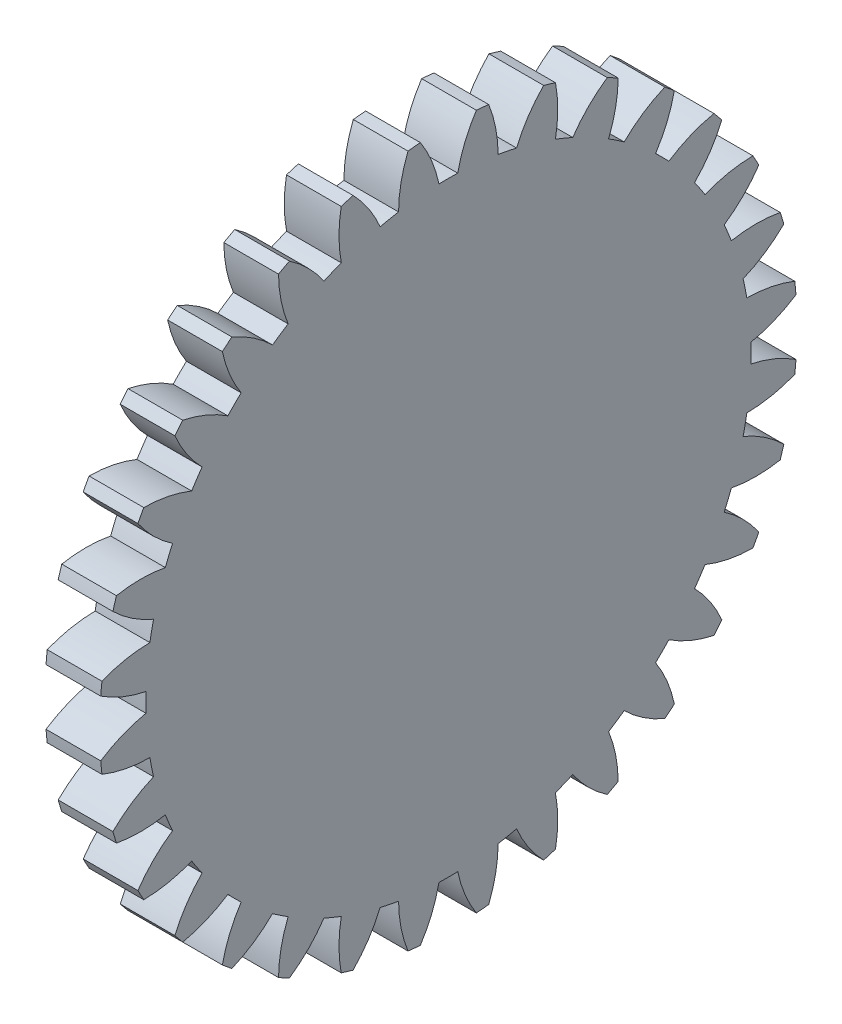
SolidWorks part; units mm, degrees
ref_plane "Plane1" through (0, 0, 0) normal (0, 0, 1) x (1, 0, 0)
ref_plane "Plane2" through (0, 0, 0) normal (0, 1, 0) x (1, 0, 0)
ref_plane "Plane3" through (0, 0, 0) normal (1, 0, 0) x (0, 0, -1)
other "Configuration Table"
sketch "HoldingSke" plane through (0, 0, 0) normal (0, 1, 0) x (1, 0, 0)
  line L0 (0, 0) -> (0.5654, -0.3533)
  line L1 (-15, 0) -> (100, 0) construction
  line L2 (0, 0) -> (-2.1039, 2.3779)
  line L3 (0, 0) -> (-11.863, 4.5341)
  line L4 (0, 0) -> (7.3237, 4.5764)
  line L5 (0, 0) -> (-46.8476, -17.4728)
  line L6 (0, 0) -> (-3.3159, -2.2372)
  line L7 (-2.1039, 2.3779) -> (8.6586, 51.2059)
  line L8 (-76.2, 54.61) -> (-75.3, 54.61)
  line L9 (-71.009, 38.7566) -> (-53.1078, 45.2721)
  line L10 (-76.2, 71.12) -> (104.1128, 71.12)
  line L11 (0, 0) -> (-4, 0)
  line L12 (-76.2, 101.6) -> (-76.147, 101.6)
  line L13 (24.9733, 27.94) -> (52.9518, 28.4284)
  line L14 (24.9733, 27.94) -> (24.9743, 27.94)
  line L15 (24.9733, 27.94) -> (100.4006, 29.5858)
  line L16 (-63.627, -1.5) -> (-12.827, -1.5)
  circle A0 centre (0, 0) radius 2.5
  circle A1 centre (0, 0) radius 22.124
  circle A2 centre (0, 0) radius 37.5
  circle A3 centre (0, 0) radius 2.5
  dimension "MHD" = 44.248
  dimension "Hub_dia" = 75
  dimension "Bore" = 5
  dimension "MBD" = 5
  dimension "Num_teeth" = 32
  dimension "Pitch" = 0.6667
  dimension "Overall_len" = 50
  dimension "Show_teeth" = 32
  dimension "Thickness" = 4
  dimension "OAL" = 50.0001
  dimension "T_dim" = 0.9
  dimension "Ap" = 20
  dimension "H" = 19.05
  dimension "Pitch_radius" = 180.3128
  dimension "Width" = 4
  dimension "Backlash" = 0.053
  dimension "Addendum_fac" = 1
  dimension "Dedendum_fac" = 1.25
  dimension "Clearance_fac" = 0.25
  dimension "Dedendum_add" = 0.001
  dimension "Module" = 1.5
sketch "BasProSke" plane through (0, 0, 0) normal (0, 1, 0) x (1, 0, 0)
  line L0 (-10, 0) -> (60, 0) construction
  line L1 (0, 0) -> (0, 25.5)
  line L2 (0, 0) -> (4, 0)
  line L3 (4, 0) -> (4, 25.5)
  line L4 (4, 25.5) -> (0, 25.5)
  dimension "Thickness" = 4
  dimension "Diameter" = 51
revolve "Base-Revolve" add sketch "BasProSke" angle 360 about L0
sketch "TooCutSke" plane through (0, 0, 0) normal (1, 0, 0) x (0, 0, -1)
  line L1 (0, 0) -> (0, 107) construction
  line L2 (0, 0) -> (-1.2704, 23.9664) construction
  line L3 (0, 0) -> (-4.7, 47.72) construction
  line L4 (-1.2704, 23.9664) -> (-2.35, 23.86) construction
  arc A0 (0.6867, 22.1133) -> (-0.6867, 22.1133) centre (0, 0) ccw
  arc A1 (2.0647, 25.4418) -> (-2.0647, 25.4418) centre (0, 0) ccw
  circle A2 centre (0, 0) radius 24 construction
  circle A3 centre (0, 0) radius 22.5526 construction
  arc A4 (-0.6867, 22.1133) -> (-2.0647, 25.4418) centre (-10.0881, 20.1706) ccw
  arc A5 (2.0647, 25.4418) -> (0.6867, 22.1133) centre (10.0881, 20.1706) ccw
  dimension "Root_dia" = 44.248
  dimension "Overcut_dia" = 51.0508
  dimension "Pitch_dia" = 48
  dimension "Base_dia" = 45.1052
  dimension "Flank_rad" = 9.6
  dimension "Half_ang" = 5.625
  dimension "Half_CT" = 1.0849
extrude "ToothCut" cut sketch "TooCutSke" along normal through all
fillet "Breaks" [suppressed] radius 0.03
fillet "RootFillets" [suppressed] radius 0.376
pattern_circular "TeethCuts" count 32 every 11.25 about axis through (-10, 0, 0) along (1, 0, 0) of "ToothCut", "RootFillets", "Breaks"
sketch "HubNeaOneSke" plane through (0, 0, 0) normal (-1, 0, 0) x (0, 0, 1)
  circle A0 centre (0, 0) radius 22.124
  dimension "Diameter" = 44.248
extrude "HubNearOne" [suppressed] add sketch "HubNeaOneSke" along normal blind 46.0001
sketch "HubNeaBotSke" plane through (0, 0, 0) normal (-1, 0, 0) x (0, 0, 1)
  circle A0 centre (0, 0) radius 22.124
  dimension "Diameter" = 44.248
extrude "HubNearBoth" [suppressed] add sketch "HubNeaBotSke" along normal blind 23
ref_plane "FarPln" through (4, 0, 0) normal (1, 0, 0) x (0, 0, -1)
sketch "HubFarSke" plane through (4, 0, 0) normal (1, 0, 0) x (0, 0, -1)
  circle A0 centre (0, 0) radius 22.124
  dimension "Diameter" = 44.248
extrude "HubFar" [suppressed] add sketch "HubFarSke" along normal blind 23
sketch "BorSke" plane through (0, 0, 0) normal (1, 0, 0) x (0, 0, -1)
  circle A0 centre (0, 0) radius 2.5
  dimension "Diameter" = 5
extrude "Bore" cut sketch "BorSke" along normal mid plane 100.0001
sketch "KeySke" plane through (0, 0, 0) normal (1, 0, 0) x (0, 0, -1)
  line L0 (-1, 0) -> (-1, 3.4)
  line L1 (-1, 3.4) -> (1, 3.4)
  line L2 (1, 3.4) -> (1, 0)
  line L3 (0, 0) -> (0, 34) construction
  line L4 (-1, 0) -> (1, 0)
  dimension "Offset" = 3.4
  dimension "Width" = 2
extrude "Keyway" [suppressed] cut sketch "KeySke" along normal mid plane 100.0001
pattern_circular "Keyway2" [suppressed] count 2 every 90 about axis through (-10, 0, 0) along (1, 0, 0)
sketch "Sketch1" plane through (0, 0, 0) normal (-1, 0, 0) x (0, 0, 1)
  circle A0 centre (0, 0) radius 2.5 construction
  circle A1 centre (0, 0) radius 2.5
extrude "Boss-Extrude1" add sketch "Sketch1" against normal up to surface (4 mm away) up to face at (4, 0, 2.5)
sketch "Sketch2" plane through (0, 0, 0) normal (-1, 0, 0) x (0, 0, 1)
  circle A0 centre (0, 0) radius 7.2
  dimension "D1" = 14.4
extrude "Cut-Extrude1" cut sketch "Sketch2" against normal blind 2
equation "' \"Module@HoldingSke\" = 6.35"
equation "' \"Num_teeth@HoldingSke\" = 12"
equation "' \"Ap@HoldingSke\" =  20"
equation "' \"Ap@HoldingSke\" = 20"
equation "' \"Width@HoldingSke\" = 0.5 * 25.4"
equation "' \"Hub_dia@HoldingSke\"= 1 * 25.4"
equation "' \"Hub_dia@HoldingSke\" = 1 * 25.4"
equation "' \"Overall_len@HoldingSke\" = 1.0 * 25.4"
equation "' \"Bore@HoldingSke\" = 0.75 * 25.4"
equation "' \"T_dim@HoldingSke\" = 0.1 * 25.4"
equation "' \"Width@KeySke\" = 0.25 * 25.4"
equation "' \"Show_teeth@HoldingSke\" = 13"
equation "' \"Backlash@HoldingSke\" = 0.009 * 25.4"
equation "' \"Addendum_fac@HoldingSke\" = 1.0"
equation "' \"Dedendum_fac@HoldingSke\" = 1.25"
equation "' \"Dedendum_add@HoldingSke\" = 0.00005 * 25.4"
equation "' \"Clearance_fac@HoldingSke\" = 0.25"
equation "\"Pitch@HoldingSke\" = 1 / \"Module@HoldingSke\""
equation "\"Overcut_dia@TooCutSke\" = (\"Num_teeth@HoldingSke\" + 2 * \"Addendum_fac@HoldingSke\") / \"Pitch@HoldingSke\" + 0.002 * 25.4"
equation "\"Pitch_dia@TooCutSke\" = \"Num_teeth@HoldingSke\" / \"Pitch@HoldingSke\""
equation "\"Base_dia@TooCutSke\" = \"Num_teeth@HoldingSke\" / \"Pitch@HoldingSke\" * cos((\"Ap@HoldingSke\"  * 3.14159265 / 180))"
equation "\"Root_dia@TooCutSke\" = (\"Num_teeth@HoldingSke\" + 2) / \"Pitch@HoldingSke\" - 2 * (\"Addendum_fac@HoldingSke\" + \"Dedendum_fac@HoldingSke\") / \"Pitch@HoldingSke\" - \"Dedendum_add@HoldingSke\" * 2"
equation "\"Half_ang@TooCutSke\" = 180 / \"Num_teeth@HoldingSke\""
equation "\"Half_CT@TooCutSke\" = \"Num_teeth@HoldingSke\" / \"Pitch@HoldingSke\" * sin((3.14159265 / 2 / \"Num_teeth@HoldingSke\")) / 2 - 7 * \"Backlash@HoldingSke\" / 4"
equation "\"Flank_rad@TooCutSke\" = \"Num_teeth@HoldingSke\" / \"Pitch@HoldingSke\" / 5"
equation "\"Radius@RootFillets\" = \"Clearance_fac@HoldingSke\" / \"Pitch@HoldingSke\" + \"Dedendum_add@HoldingSke\""
equation "\"Break_rad@Breaks\" = 0.02 / \"Pitch@HoldingSke\""
equation "\"Thickness@HoldingSke\" = \"Width@HoldingSke\""
equation "\"OAL@HoldingSke\" = \"Thickness@HoldingSke\""
equation "\"MHD@HoldingSke\" = (\"Num_teeth@HoldingSke\" + 2) / \"Pitch@HoldingSke\" - 2 * (\"Addendum_fac@HoldingSke\" + \"Dedendum_fac@HoldingSke\")  / \"Pitch@HoldingSke\" - \"Dedendum_add@HoldingSke\" * 2"
equation "\"MBD@HoldingSke\" = (\"Num_teeth@HoldingSke\" + 2) / \"Pitch@HoldingSke\" - 2 * (\"Addendum_fac@HoldingSke\" + \"Dedendum_fac@HoldingSke\")  / \"Pitch@HoldingSke\" - \"Dedendum_add@HoldingSke\" * 2 - 0.002 * 25.4"
equation "\"MHD@HoldingSke\" = ((sgn( \"MHD@HoldingSke\" - \"Hub_dia@HoldingSke\" )-1)*( \"MHD@HoldingSke\" - \"Hub_dia@HoldingSke\" ))/-2+ \"Hub_dia@HoldingSke\""
equation "\"MBD@HoldingSke\" = ((sgn( \"MBD@HoldingSke\" - \"Bore@HoldingSke\" )-1)*( \"MBD@HoldingSke\" - \"Bore@HoldingSke\" ))/-2+ \"Bore@HoldingSke\""
equation "\"OAL@HoldingSke\" = ((sgn( \"OAL@HoldingSke\" - \"Overall_len@HoldingSke\" )+1)*( \"OAL@HoldingSke\" - \"Overall_len@HoldingSke\" ))/2 + \"Overall_len@HoldingSke\" + 0.000002 * 25.4"
equation "\"Num_teeth@TeethCuts\" = int( \"Show_teeth@HoldingSke\" ) + 1"
equation "\"Num_teeth@TeethCuts\" = ((sgn( \"Num_teeth@TeethCuts\" - \"Num_teeth@HoldingSke\" )-1)*( \"Num_teeth@TeethCuts\" - \"Num_teeth@HoldingSke\" ))/-2+ \"Num_teeth@HoldingSke\""
equation "\"Num_teeth@TeethCuts\" = ((sgn( \"Num_teeth@TeethCuts\" - 2.0)+1)*( \"Num_teeth@TeethCuts\" - 2.0))/2 +2.0"
equation "\"Angle@TeethCuts\" = 360.0 / \"Num_teeth@HoldingSke\""
equation "\"Diameter@BasProSke\" = (\"Num_teeth@HoldingSke\" + 2 * \"Addendum_fac@HoldingSke\") / \"Pitch@HoldingSke\""
equation "\"Thickness@BasProSke\"  = \"Thickness@HoldingSke\""
equation "' \"Fillet_rad@BasProSke\" =  \"Thickness@HoldingSke\" * 0.05"
equation "' \"Fillet_rad@BasProSke\" = \"Thickness@HoldingSke\" * 0.05"
equation "\"MHD@HoldingSke\" = ((sgn( \"MHD@HoldingSke\" - \"Root_dia@TooCutSke\" )-1)*( \"MHD@HoldingSke\" - \"Root_dia@TooCutSke\" ))/-2+ \"Root_dia@TooCutSke\""
equation "\"Diameter@HubNeaOneSke\" = \"MHD@HoldingSke\""
equation "\"Length@HubNearOne\" = \"OAL@HoldingSke\" - \"Thickness@BasProSke\""
equation "\"Diameter@HubNeaBotSke\" = \"MHD@HoldingSke\""
equation "\"Length@HubNearBoth\" = ( \"OAL@HoldingSke\" - \"Thickness@BasProSke\" ) / 2.0"
equation "\"Thickness@FarPln\" = \"Thickness@BasProSke\""
equation "\"Diameter@HubFarSke\" = \"MHD@HoldingSke\""
equation "\"Length@HubFar\" = ( \"OAL@HoldingSke\" - \"Thickness@BasProSke\" ) / 2.0"
equation "\"Diameter@BorSke\" = \"MBD@HoldingSke\""
equation "\"D1@Bore\" = \"OAL@HoldingSke\" * 2.0"
equation "\"D1@Keyway\" = \"OAL@HoldingSke\" * 2.0"
equation "\"Offset@KeySke\" = \"T_dim@HoldingSke\" + \"MBD@HoldingSke\" / 2.0"
